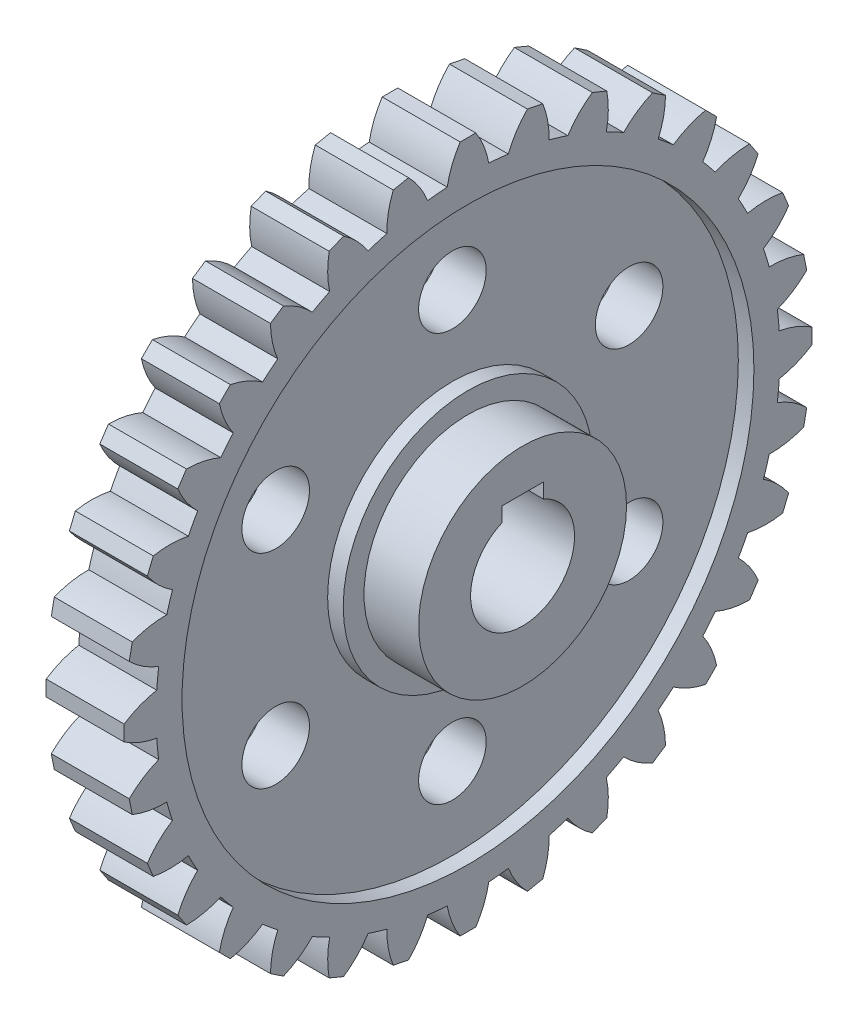
SolidWorks part; units mm, degrees
ref_plane "Ebene vorne" through (0, 0, 0) normal (0, 0, 1) x (1, 0, 0)
ref_plane "Ebene oben" through (0, 0, 0) normal (0, 1, 0) x (1, 0, 0)
ref_plane "Ebene rechts" through (0, 0, 0) normal (1, 0, 0) x (0, 0, -1)
sketch "Sketch1" plane through (0, 0, 0) normal (1, 0, 0) x (0, 0, -1)
  circle A0 centre (0, 0) radius 60
  dimension "D1" = 120
extrude "Boss-Extrude1" add sketch "Sketch1" along normal mid plane 15
sketch "Sketch2" plane through (7.5, 0, 0) normal (1, 0, 0) x (0, 0, -1)
  line L0 (0, 0) -> (0, 90.3269) construction
  line L1 (-1.5, 66.1365) -> (1.5, 66.1365)
  circle A0 centre (0, 0) radius 60 construction
  circle A1 centre (0, 0) radius 60
  arc A2 (-4, 59.8665) -> (4, 59.8665) centre (0, 0) cw
  arc A3 (-1.5, 66.1365) -> (-4, 59.8665) centre (12.7267, 56.8306) ccw
  arc A4 (1.5, 66.1365) -> (4, 59.8665) centre (-12.7267, 56.8306) cw
  dimension "D4" = 17
  dimension "D1" = 1.5
  dimension "D2" = 4
  dimension "D3" = 6.27
extrude "Boss-Extrude2" add sketch "Sketch2" against normal up to surface (15 mm away) contours A4 A2 A3 L1 up to face at (-7.5, 0, -60)
pattern_circular "CirPattern1" count 32 over 360 about axis through (0, 0, 0) along (1, 0, 0) of "Boss-Extrude2"
sketch "Sketch3" plane through (0, 0, 0) normal (1, 0, 0) x (0, 0, -1)
  circle A0 centre (0, 0) radius 20
  dimension "D1" = 40
extrude "Boss-Extrude3" add sketch "Sketch3" along normal mid plane 36
sketch "Sketch4" plane through (18, 0, 0) normal (1, 0, 0) x (0, 0, -1)
  line L0 (0, 0) -> (0, 28.3085) construction
  line L1 (-4, 12) -> (4, 12)
  line L2 (4, 9.1652) -> (4, 12)
  line L3 (-4, 9.1652) -> (-4, 12)
  arc A0 (-4, 9.1652) -> (4, 9.1652) centre (0, 0) ccw
  point P7 (0, 0)
  point P9 (0, 0)
  point P10 (0, 0)
  dimension "D1" = 20
  dimension "D2" = 12
  dimension "D3" = 8
extrude "Cut-Extrude1" cut sketch "Sketch4" against normal through all contours A0 L2 L1 L3
sketch "Sketch5" plane through (7.5, 0, 0) normal (1, 0, 0) x (0, 0, -1)
  circle A0 centre (0, 0) radius 24
  circle A1 centre (0, 0) radius 55
  dimension "D1" = 110
  dimension "D2" = 48
extrude "Cut-Extrude6" cut sketch "Sketch5" against normal blind 3 contours A1 | A0
sketch "Sketch6" plane through (4.5, 0, 0) normal (1, 0, 0) x (0, 0, -1)
  circle A0 centre (0, 0) radius 39.25 construction
  circle A1 centre (0, 39.25) radius 6.5
  circle A2 centre (33.9915, 19.625) radius 6.5
  circle A3 centre (33.9915, -19.625) radius 6.5
  circle A4 centre (0, -39.25) radius 6.5
  circle A5 centre (-33.9915, -19.625) radius 6.5
  circle A6 centre (-33.9915, 19.625) radius 6.5
  point P17 (0, 0)
  dimension "D1" = 78.5
  dimension "D2" = 13
  dimension "D3" = 6
extrude "Cut-Extrude7" cut sketch "Sketch6" against normal through all
mirror "Mirror1" about plane through (0, 0, 0) normal (1, 0, 0) of "Cut-Extrude6"
